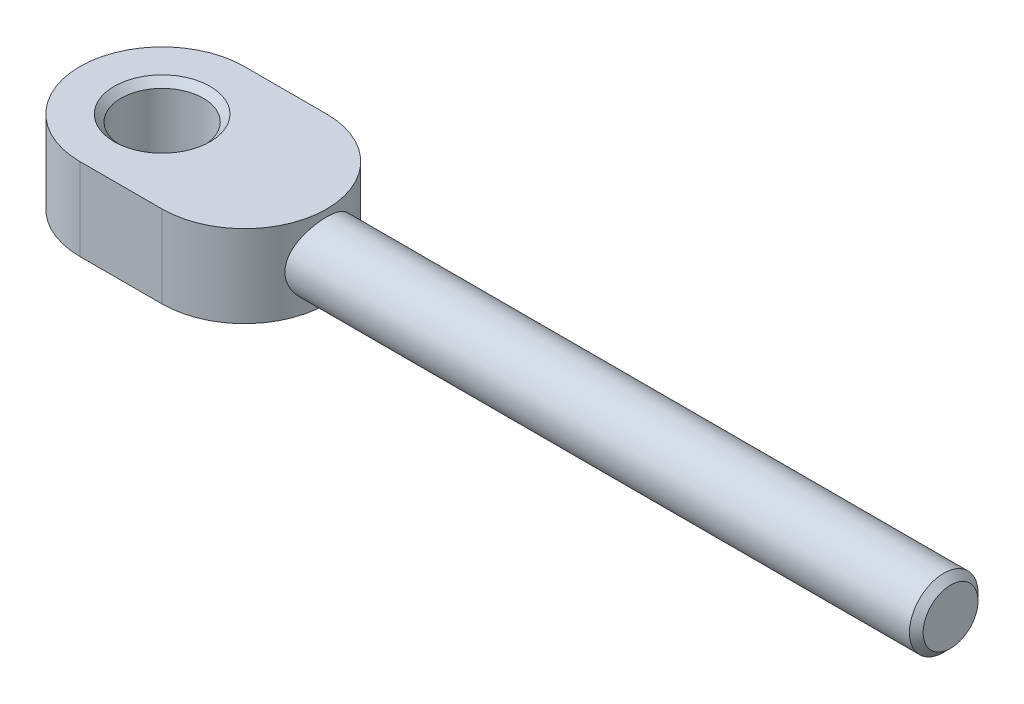
SolidWorks part; units mm, degrees
ref_plane "Piano frontale" through (0, 0, 0) normal (0, 0, 1) x (1, 0, 0)
ref_plane "Piano superiore" through (0, 0, 0) normal (0, 1, 0) x (1, 0, 0)
ref_plane "Piano destro" through (0, 0, 0) normal (1, 0, 0) x (0, 0, -1)
sketch "Schizzo1" plane through (0, 0, 0) normal (1, 0, 0) x (0, 0, -1)
  circle A0 centre (0, 0) radius 5
  dimension "D1" = 10
extrude "Estrusione-Estrusione1" add sketch "Schizzo1" along normal blind 115
sketch "Schizzo2" plane through (0, 0, 0) normal (0, 1, 0) x (1, 0, 0)
  line L0 (0, 0) -> (12, 0) construction
  line L1 (0, 12) -> (12, 12)
  line L2 (0, -12) -> (12, -12)
  line L3 (0, 5) -> (0, -5) construction
  arc A0 (0, 12) -> (0, -12) centre (0, 0) ccw
  arc A1 (12, -12) -> (12, 12) centre (12, 0) ccw
  point P3 (6, 0)
  dimension "D1" = 24
  dimension "D2" = 12
extrude "Estrusione-Estrusione2" add sketch "Schizzo2" along normal mid plane 12
sketch "Schizzo3" plane through (0, 6, 0) normal (0, 1, 0) x (1, 0, 0)
  circle A0 centre (0, 0) radius 6
  dimension "D1" = 12
extrude "Taglio-Estrusione1" cut sketch "Schizzo3" against normal up to next
chamfer "Smusso1" distance 1 angle 45 3 edges at (115, 0, -5) (0, -6, 6) (0, 6, 6)
